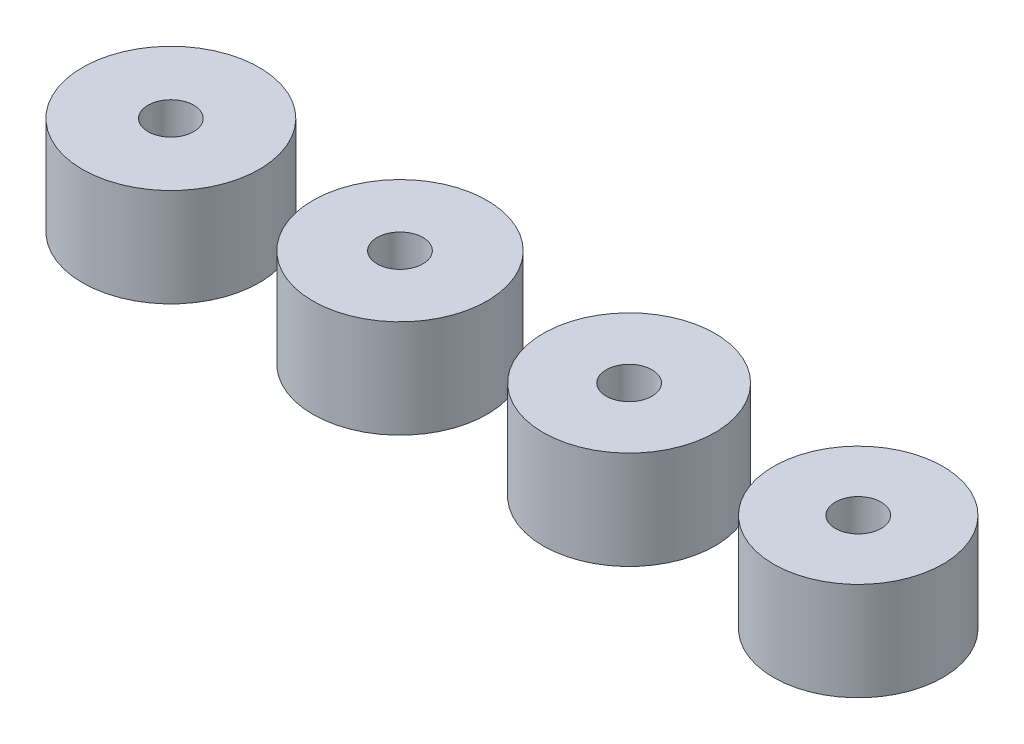
SolidWorks part; units mm, degrees
ref_plane "Płaszczyzna przednia" through (0, 0, 0) normal (0, 0, 1) x (1, 0, 0)
ref_plane "Płaszczyzna górna" through (0, 0, 0) normal (0, 1, 0) x (1, 0, 0)
ref_plane "Płaszczyzna prawa" through (0, 0, 0) normal (1, 0, 0) x (0, 0, -1)
sketch "Szkic1" plane through (0, 6, 0) normal (0, 1, 0) x (1, 0, 0)
  circle A0 centre (0, -302.8002) radius 5.4
  circle A1 centre (14, -302.8002) radius 5.325
  circle A2 centre (28, -302.8002) radius 5.25
  circle A3 centre (42, -302.8002) radius 5.175
  circle A4 centre (0, -302.8002) radius 1.4
  circle A5 centre (14, -302.8002) radius 1.4
  circle A6 centre (28, -302.8002) radius 1.4
  circle A7 centre (42, -302.8002) radius 1.4
  dimension "D1" = 14
  dimension "D2" = 14
  dimension "D3" = 14
  dimension "D4" = 10.8
  dimension "D5" = 10.65
  dimension "D6" = 10.5
  dimension "D7" = 10.35
  dimension "D8" = 2.8
  dimension "D9" = 2.8
  dimension "D10" = 2.8
  dimension "D11" = 2.8
extrude "Dodanie-wyciągnięcie1" add sketch "Szkic1" along normal blind 6
